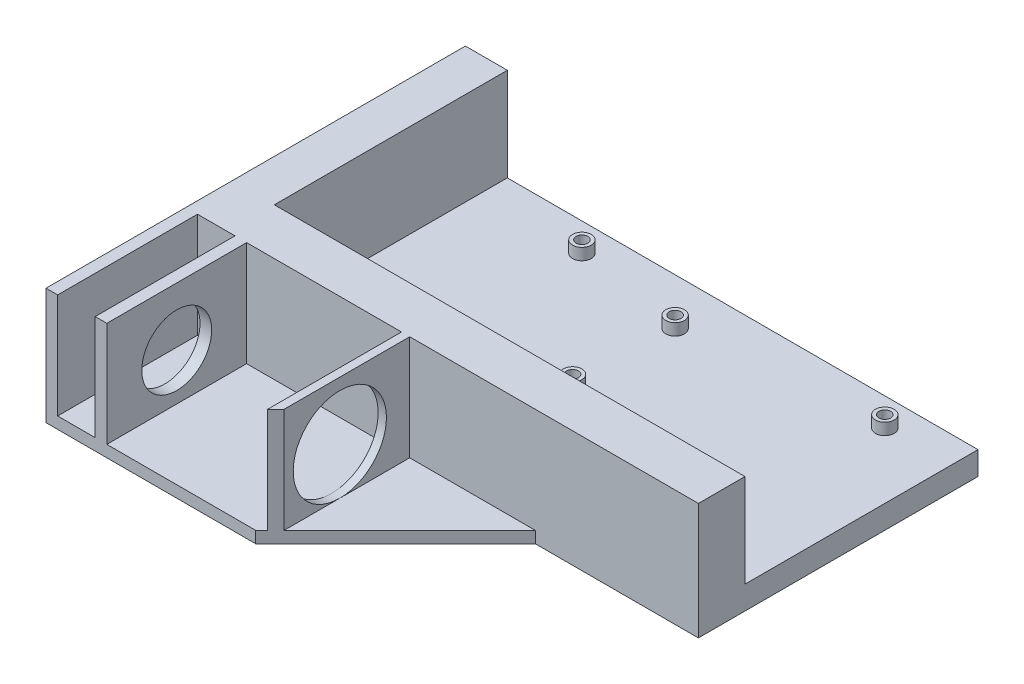
SolidWorks part; units mm, degrees
ref_plane "Front Plane" through (0, 0, 0) normal (0, 0, 1) x (1, 0, 0)
ref_plane "Top Plane" through (0, 0, 0) normal (0, 1, 0) x (1, 0, 0)
ref_plane "Right Plane" through (0, 0, 0) normal (1, 0, 0) x (0, 0, -1)
sketch "Sketch1" plane through (0, 0, 0) normal (0, 1, 0) x (1, 0, 0)
  line L0 (-69.85, -38.1) -> (69.85, -38.1)
  line L1 (-69.85, -38.1) -> (-69.85, 38.1)
  line L2 (69.85, -38.1) -> (69.85, 38.1)
  line L3 (-69.85, 38.1) -> (69.85, 38.1)
  line L4 (-69.85, -38.1) -> (69.85, 38.1) construction
  line L5 (69.85, -38.1) -> (-69.85, 38.1) construction
  line L10 (-58.42, -26.67) -> (58.42, 26.67) construction
  line L11 (58.42, -26.67) -> (-58.42, 26.67) construction
  point P1 (0, 0)
  point P2 (0, 0)
  dimension "D1" = 76.2
  dimension "D2" = 139.7
extrude "Boss-Extrude1" add sketch "Sketch1" along normal blind 31.75
sketch "Sketch2" plane through (0, 31.75, 0) normal (0, 1, 0) x (1, 0, 0)
  line L0 (-58.42, -25.4) -> (69.85, -25.4)
  line L1 (-58.42, -25.4) -> (-58.42, 38.1459)
  line L2 (69.85, -25.4) -> (69.85, 38.1459)
  line L3 (-58.42, 38.1459) -> (69.85, 38.1459)
  line L4 (69.85, -38.1) -> (69.85, 38.1) construction
  line L5 (-69.85, 38.1) -> (-69.85, -38.1) construction
  line L9 (-69.85, -38.1) -> (69.85, -38.1) construction
  dimension "D1" = 11.43
  dimension "D2" = 12.7
extrude "Cut-Extrude1" cut sketch "Sketch2" against normal blind 25.4
sketch "Sketch3" plane through (0, 6.35, 0) normal (0, 1, 0) x (1, 0, 0)
  line L0 (-58.42, -25.4) -> (-48.26, -25.4)
  line L1 (-58.42, -25.4) -> (-58.42, -15.24)
  line L2 (-48.26, -25.4) -> (-48.26, -15.24)
  line L3 (-58.42, -15.24) -> (-48.26, -15.24)
  line L4 (-58.42, -25.4) -> (69.85, -25.4) construction
  dimension "D1" = 10.16
  dimension "D2" = 10.16
extrude "Boss-Extrude3" add sketch "Sketch3" along normal blind 12.7
sketch "Sketch4" plane through (0, 19.05, 0) normal (0, 1, 0) x (1, 0, 0)
  line L0 (-48.26, -25.4) -> (-48.26, -15.24) construction
  line L1 (-48.26, -15.24) -> (-58.42, -15.24) construction
  circle A0 centre (-53.34, -20.32) radius 2.032
  point P4 (-48.26, -20.32)
  dimension "D1" = 4.064
  dimension "D2" = 5.08
  dimension "D3" = 5.08
extrude "Cut-Extrude2" cut sketch "Sketch4" against normal through all
sketch "Sketch5" plane through (0, 19.05, 0) normal (0, 1, 0) x (1, 0, 0)
  circle A0 centre (-53.34, -20.32) radius 3.937
extrude "Cut-Extrude3" cut sketch "Sketch5" against normal blind 2.286
sketch "Sketch7" plane through (0, 6.35, 0) normal (0, 1, 0) x (1, 0, 0)
  line L1 (-58.42, 38.1) -> (69.85, 38.1) construction
  circle A0 centre (-30.48, 30.48) radius 1.6002
  circle A1 centre (-24.13, -17.78) radius 1.6002
  circle A2 centre (0, -2.54) radius 1.6002
  circle A3 centre (0, 25.4) radius 1.6002
  circle A4 centre (52.07, 30.48) radius 1.6002
  circle A5 centre (50.8, -17.78) radius 1.6002
  circle A6 centre (-30.48, 30.48) radius 2.54
  circle A7 centre (-24.13, -17.78) radius 2.54
  circle A8 centre (0, 25.4) radius 2.54
  circle A9 centre (0, -2.54) radius 2.54
  circle A10 centre (50.8, -17.78) radius 2.54
  circle A11 centre (52.07, 30.48) radius 2.54
  point P15 (0, 0)
  point P20 (0, 25.4)
  dimension "D1" = 3.2004
  dimension "D10" = 5.08
  dimension "D2" = 6.35
  dimension "D3" = 48.26
  dimension "D4" = 30.48
  dimension "D5" = 5.08
  dimension "D6" = 27.94
  dimension "D7" = 74.93
  dimension "D8" = 82.55
  dimension "D9" = 7.62
extrude "Boss-Extrude5" add sketch "Sketch7" along normal blind 3.175
sketch "Sketch8" plane through (0, 0, 0) normal (0, -1, 0) x (1, 0, 0)
  line L0 (-69.85, 38.1) -> (-69.85, 76.2)
  line L1 (-69.85, 76.2) -> (-12.7, 76.2)
  line L2 (-12.7, 76.2) -> (25.4, 38.1)
  line L3 (-69.85, 38.1) -> (69.85, 38.1) construction
  line L4 (25.4, 38.1) -> (-69.85, 38.1)
  dimension "D1" = 95.25
  dimension "D2" = 57.15
  dimension "D3" = 38.1
extrude "Boss-Extrude6" add sketch "Sketch8" against normal blind 3.175
sketch "Sketch9" plane through (0, 3.175, 0) normal (0, 1, 0) x (1, 0, 0)
  line L0 (-69.85, -38.1) -> (25.4, -38.1) construction
  line L1 (-69.85, -76.2) -> (-66.675, -76.2)
  line L2 (-69.85, -76.2) -> (-69.85, -38.1)
  line L3 (-69.85, -38.1) -> (-66.675, -38.1)
  line L4 (-66.675, -76.2) -> (-66.675, -38.1)
  line L5 (-12.7, -76.2) -> (-69.85, -76.2) construction
  line L6 (-8.8265, -72.3265) -> (-11.0716, -74.5716)
  line L7 (-8.8265, -72.3265) -> (-8.8265, -38.1)
  line L8 (-8.8265, -38.1) -> (-11.0716, -38.1)
  line L9 (-11.0716, -74.5716) -> (-11.0716, -38.1)
  line L10 (-56.4515, -76.2) -> (-53.2765, -76.2)
  line L11 (-56.4515, -76.2) -> (-56.4515, -38.1)
  line L12 (-56.4515, -38.1) -> (-53.2765, -38.1)
  line L13 (-53.2765, -76.2) -> (-53.2765, -38.1)
  line L14 (25.4, -38.1) -> (-12.7, -76.2) construction
  point P18 (0, 0)
  dimension "D1" = 3.175
  dimension "D2" = 13.3985
  dimension "D3" = 44.45
extrude "Boss-Extrude7" add sketch "Sketch9" along normal up to surface (28.575 mm away) up to face at (-19.4733, 31.75, 8.4667)
sketch "Sketch10" plane through (-69.85, 0, 0) normal (-1, 0, 0) x (0, 0, 1)
  line L0 (76.2, 31.75) -> (76.2, 0) construction
  line L3 (-38.1, 0) -> (76.2, 0) construction
  circle A0 centre (57.15, 15.875) radius 5.5499
  point P2 (0, 0)
  point P9 (0, 0)
  point P10 (0, 0)
  dimension "D1" = 11.0998
  dimension "D2" = 19.05
  dimension "D3" = 15.875
extrude "Cut-Extrude4" cut sketch "Sketch10" against normal blind 3.175
sketch "Sketch11" plane through (-56.4515, 0, 0) normal (-1, 0, 0) x (0, 0, 1)
  line L2 (-38.1, 0) -> (76.2, 0) construction
  line L3 (76.2, 31.75) -> (76.2, 0) construction
  circle A0 centre (57.15, 15.875) radius 9.525
  point P2 (0, 0)
  point P6 (0, 0)
  point P10 (0, 0)
  dimension "D1" = 19.05
  dimension "D2" = 15.875
  dimension "D3" = 19.05
extrude "Cut-Extrude5" cut sketch "Sketch11" against normal blind 3.175
sketch "Sketch12" plane through (-11.0716, 0, 0) normal (-1, 0, 0) x (0, 0, 1)
  line L5 (38.1, 31.75) -> (38.1, 3.175) construction
  line L6 (-38.1, 0) -> (76.2, 0) construction
  circle A0 centre (57.15, 15.875) radius 12.7
  point P5 (0, 0)
  point P9 (0, 0)
  dimension "D1" = 25.4
  dimension "D2" = 19.05
  dimension "D3" = 15.875
extrude "Cut-Extrude6" cut sketch "Sketch12" against normal blind 3.175
